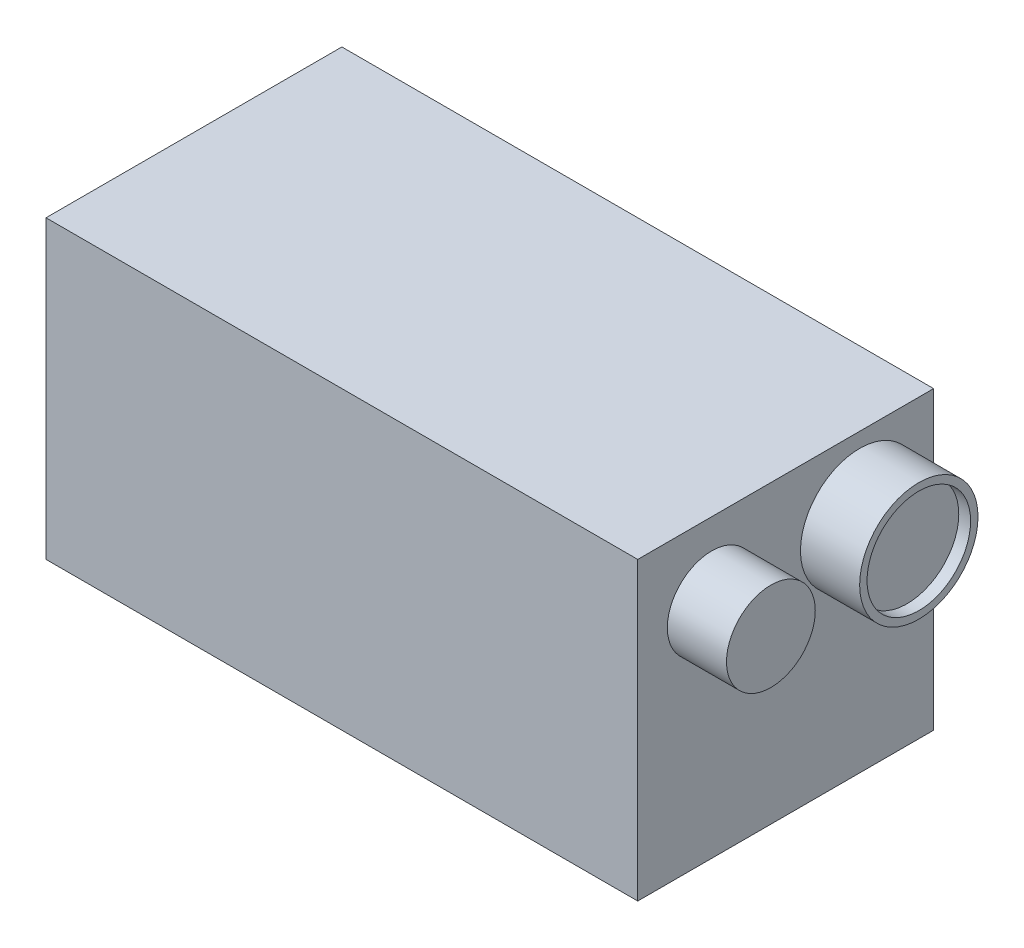
SolidWorks part; units mm, degrees
ref_plane "정면" through (0, 0, 0) normal (0, 0, 1) x (1, 0, 0)
ref_plane "윗면" through (0, 0, 0) normal (0, 1, 0) x (1, 0, 0)
ref_plane "우측면" through (0, 0, 0) normal (1, 0, 0) x (0, 0, -1)
sketch "스케치1" plane through (0, 0, 0) normal (0, 0, 1) x (1, 0, 0)
  line L1 (50, -25) -> (-50, -25)
  line L2 (50, -25) -> (50, 25)
  line L3 (50, 25) -> (-50, 25)
  line L4 (-50, -25) -> (-50, 25)
  line L5 (50, -25) -> (-50, 25) construction
  line L6 (50, 25) -> (-50, -25) construction
  point P0 (0, 0)
  dimension "D1" = 50
  dimension "D2" = 100
extrude "보스-돌출1" add sketch "스케치1" along normal mid plane 50
sketch "스케치2" plane through (50, 0, 0) normal (1, 0, 0) x (0, 0, -1)
  line L0 (25, 25) -> (-25, -25)
  line L1 (-25, 25) -> (25, -25)
  line L2 (25, 0) -> (-25, 0)
  line L3 (25, -25) -> (25, 25) construction
  line L4 (-25, -25) -> (-25, 25) construction
  line L5 (0, 25) -> (0, -25)
  line L6 (-25, 25) -> (25, 25) construction
  line L7 (-25, -25) -> (25, -25) construction
  line L8 (0, 25) -> (25, 0)
  line L9 (-25, 0) -> (0, 25)
  circle A0 centre (12.5, 12.5) radius 10
  circle A1 centre (-12.5, 12.5) radius 7.5
  dimension "D1" = 20
  dimension "D2" = 15
extrude "보스-돌출2" add sketch "스케치2" along normal blind 10 contours A1 | A0
sketch "스케치3" plane through (60, 0, 0) normal (1, 0, 0) x (0, 0, -1)
  line L0 (12.5, 12.5) -> (2.5, 12.5)
  line L1 (-5, 12.5) -> (-12.5, 12.5)
  circle A0 centre (12.5, 12.5) radius 10 construction
  circle A1 centre (12.5, 12.5) radius 8.75
  circle A2 centre (-12.5, 12.5) radius 7.5 construction
  dimension "D1" = 17.5
extrude "컷-돌출1" cut sketch "스케치3" against normal blind 2
